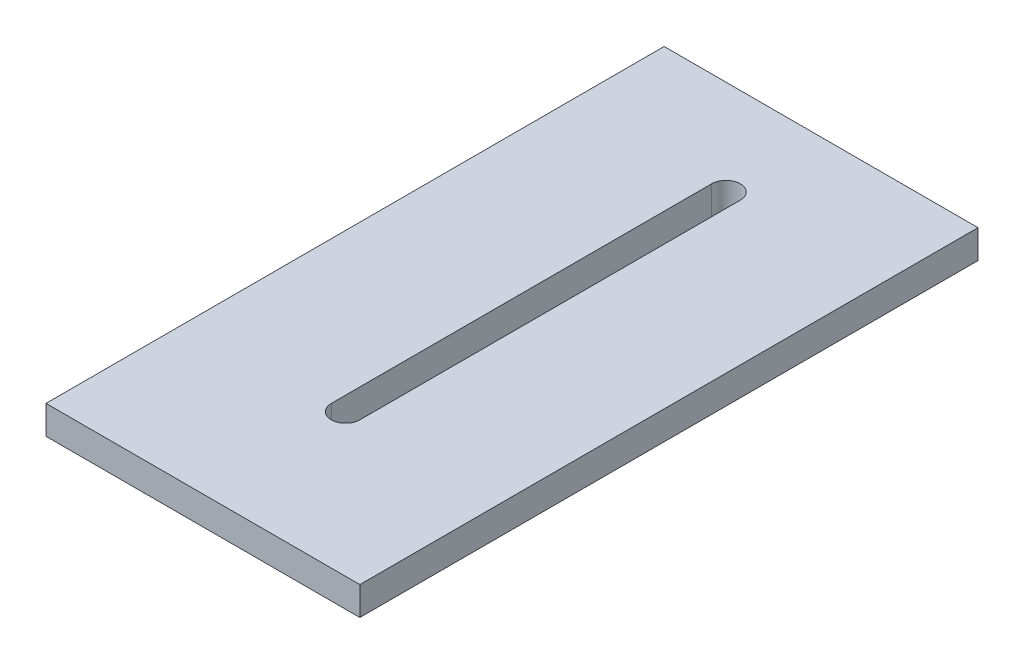
SolidWorks part; units mm, degrees
ref_plane "前视基准面" through (0, 0, 0) normal (0, 0, 1) x (1, 0, 0)
ref_plane "上视基准面" through (0, 0, 0) normal (0, 1, 0) x (1, 0, 0)
ref_plane "右视基准面" through (0, 0, 0) normal (1, 0, 0) x (0, 0, -1)
sketch "草图2" plane through (0, 0, 0) normal (0, 1, 0) x (1, 0, 0)
  line L0 (16.5, 55.771) -> (16.5, 12.0839) construction
  line L5 (0, 0) -> (33, 0)
  line L11 (0, 0) -> (0, 65)
  line L25 (0, 65) -> (33, 65)
  line L26 (33, 0) -> (33, 65)
  line L27 (15, 15) -> (15, 55)
  line L28 (18, 55) -> (18, 15)
  arc A0 (18, 55) -> (15, 55) centre (16.5, 55) ccw
  arc A1 (15, 15) -> (18, 15) centre (16.5, 15) ccw
  dimension "D3" = 16.5
  dimension "D1" = 33
  dimension "D2" = 65
  dimension "D4" = 40
  dimension "D5" = 10
extrude "凸台-拉伸1" add sketch "草图2" along normal blind 3
